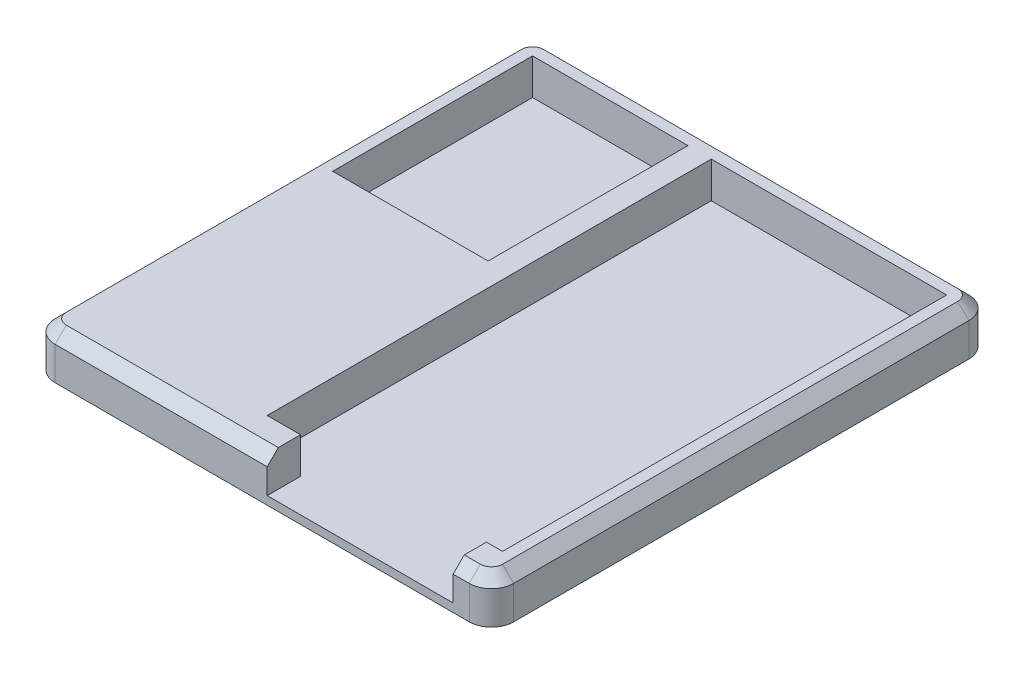
SolidWorks part; units mm, degrees
ref_plane "Front Plane" through (0, 0, 0) normal (0, 0, 1) x (1, 0, 0)
ref_plane "Top Plane" through (0, 0, 0) normal (0, 1, 0) x (1, 0, 0)
ref_plane "Right Plane" through (0, 0, 0) normal (1, 0, 0) x (0, 0, -1)
sketch "Sketch1" plane through (0, 0, 0) normal (0, 1, 0) x (1, 0, 0)
  line L1 (52.451, 57.15) -> (-52.451, 57.15)
  line L2 (52.451, 57.15) -> (52.451, -57.15)
  line L3 (52.451, -57.15) -> (-52.451, -57.15)
  line L4 (-52.451, 57.15) -> (-52.451, -57.15)
  line L5 (52.451, 57.15) -> (-52.451, -57.15) construction
  line L6 (52.451, -57.15) -> (-52.451, 57.15) construction
  point P0 (0, 0)
  dimension "D1" = 104.902
  dimension "D2" = 114.3
extrude "Boss-Extrude1" add sketch "Sketch1" along normal blind 10.16
sketch "Sketch2" plane through (0, 10.16, 0) normal (0, 1, 0) x (1, 0, 0)
  line L0 (-52.451, 57.15) -> (-52.451, -57.15) construction
  line L1 (-47.371, 52.07) -> (-11.811, 52.07)
  line L2 (-47.371, 52.07) -> (-47.371, 6.35)
  line L3 (-47.371, 6.35) -> (-11.811, 6.35)
  line L4 (-11.811, 52.07) -> (-11.811, 6.35)
  line L5 (-47.371, 52.07) -> (-11.811, 6.35) construction
  line L6 (-47.371, 6.35) -> (-11.811, 52.07) construction
  line L7 (52.451, 57.15) -> (-52.451, 57.15) construction
  point P0 (-29.591, 29.21)
  dimension "D1" = 35.56
  dimension "D2" = 45.72
  dimension "D3" = 5.08
  dimension "D4" = 5.08
extrude "Cut-Extrude1" cut sketch "Sketch2" against normal blind 8.255
sketch "Sketch3" plane through (0, 10.16, 0) normal (0, 1, 0) x (1, 0, 0)
  line L0 (52.451, 57.15) -> (-52.451, 57.15) construction
  line L1 (-6.477, 52.07) -> (47.371, 52.07)
  line L2 (-6.477, 52.07) -> (-6.477, -49.53)
  line L3 (-6.477, -49.53) -> (47.371, -49.53)
  line L4 (47.371, 52.07) -> (47.371, -49.53)
  line L5 (-6.477, 52.07) -> (47.371, -49.53) construction
  line L6 (-6.477, -49.53) -> (47.371, 52.07) construction
  line L7 (52.451, -57.15) -> (52.451, 57.15) construction
  point P0 (20.447, 1.27)
  dimension "D1" = 53.848
  dimension "D2" = 101.6
  dimension "D3" = 5.08
  dimension "D4" = 5.08
extrude "Cut-Extrude2" cut sketch "Sketch3" against normal blind 8.255
sketch "Sketch4" plane through (0, 10.16, 0) normal (0, 1, 0) x (1, 0, 0)
  line L0 (-6.477, -49.53) -> (47.371, -49.53) construction
  line L1 (1.143, -49.53) -> (13.843, -49.53)
  line L2 (1.143, -49.53) -> (1.143, -57.15)
  line L3 (1.143, -57.15) -> (15.4686, -57.15)
  line L5 (-52.451, -57.15) -> (52.451, -57.15) construction
  line L6 (-6.477, 52.07) -> (-6.477, -49.53) construction
  line L7 (47.371, -49.53) -> (47.371, 52.07) construction
  line L8 (33.528, -49.53) -> (43.688, -49.53)
  line L10 (33.528, -57.15) -> (43.688, -57.15)
  line L11 (43.688, -49.53) -> (43.688, -57.15)
  line L12 (13.843, -49.53) -> (33.528, -49.53)
  line L13 (15.4686, -57.15) -> (33.528, -57.15)
  dimension "D1" = 12.7
  dimension "D2" = 7.62
  dimension "D3" = 10.16
  dimension "D4" = 3.683
extrude "Cut-Extrude3" cut sketch "Sketch4" against normal blind 8.255
fillet "Fillet1" radius 5.08 4 edges at (52.451, 5.08, 57.15) (-52.451, 5.08, 57.15) (-52.451, 5.08, -57.15) (52.451, 5.08, -57.15)
chamfer "Chamfer1" distance 2.54 angle 45 9 edges at (45.5295, 10.16, 57.15) (50.9631, 10.16, 55.6621) (52.451, 10.16, 0) (50.9631, 10.16, -55.6621) (0, 10.16, -57.15) (-23.114, 10.16, 57.15) (-50.9631, 10.16, -55.6621) (-50.9631, 10.16, 55.6621) (-52.451, 10.16, 0)
